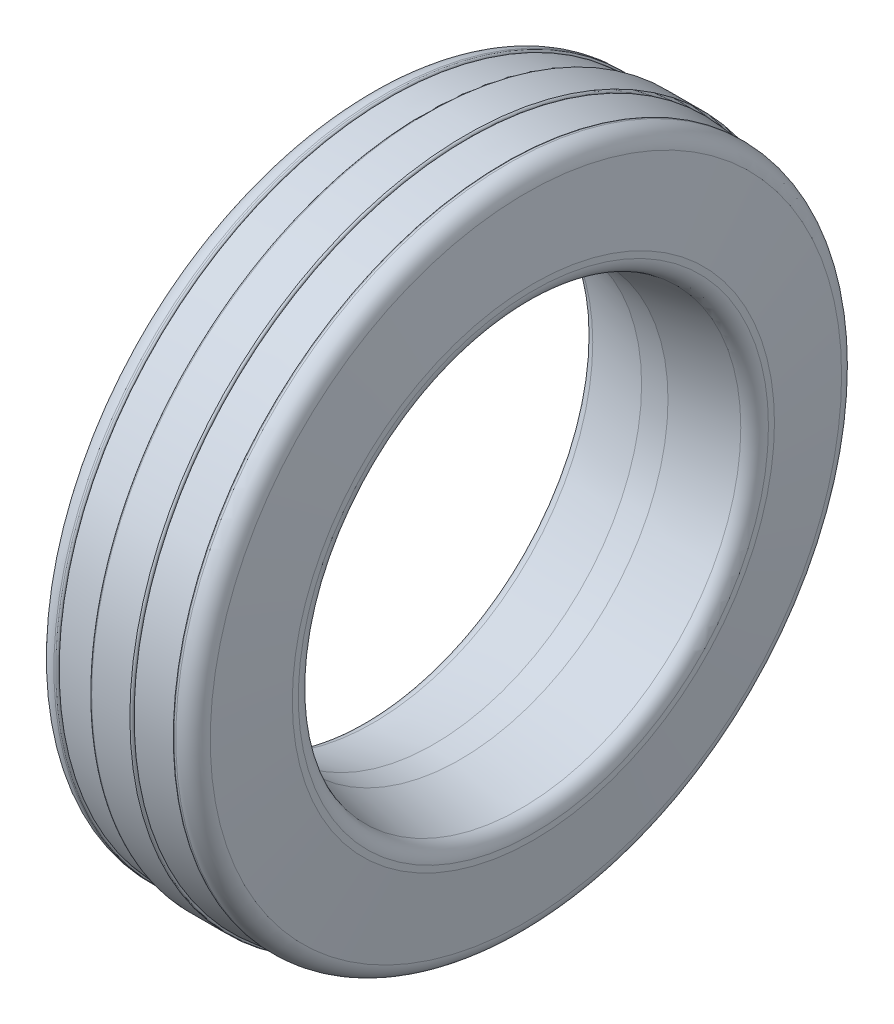
SolidWorks part; units mm, degrees
material "PE High Density"
ref_plane "Front Plane" through (0, 0, 0) normal (0, 0, 1) x (1, 0, 0)
ref_plane "Top Plane" through (0, 0, 0) normal (0, 1, 0) x (1, 0, 0)
ref_plane "Right Plane" through (0, 0, 0) normal (1, 0, 0) x (0, 0, -1)
sketch "Sketch1" plane through (0, 0, 0) normal (0, 1, 0) x (1, 0, 0)
  line L0 (0, 26.4614) -> (0, 26.5)
  line L1 (2.81, 36.5) -> (3.0064, 36.5)
  line L2 (19.0123, 26.5) -> (19.0123, 26.4614)
  line L3 (22, 0) -> (0, 0) construction
  line L4 (0, 26.4614) -> (0, 25.8384)
  line L5 (0.8199, 34.699) -> (0, 26.5)
  line L6 (19.0123, 26.4614) -> (19.0123, 25.8384)
  line L7 (18.1924, 34.699) -> (19.0123, 26.5)
  line L8 (13.8264, 36.5) -> (15.8264, 36.3)
  line L13 (5.1864, 36.5) -> (7.1864, 36.7)
  line L15 (3.1864, 36.32) -> (3.1864, 36.3)
  line L16 (16.0064, 36.5) -> (16.2023, 36.5)
  line L17 (15.8264, 36.32) -> (15.8264, 36.3)
  line L19 (13.8264, 36.5) -> (11.8264, 36.7)
  line L20 (7.4064, 36.95) -> (11.6064, 36.95)
  line L21 (7.1864, 36.7) -> (7.1864, 36.73)
  line L22 (11.8264, 36.7) -> (11.8264, 36.73)
  line L23 (3.1864, 36.3) -> (5.1864, 36.5)
  line L35 (10.9576, 22.8514) -> (17.6415, 24.1705)
  line L36 (10.9576, 22.8514) -> (8.0553, 22.8514)
  line L37 (8.0553, 22.8514) -> (1.3709, 24.1706)
  arc A0 (0.8199, 34.699) -> (2.81, 36.5) centre (2.81, 34.5) cw
  arc A1 (18.1924, 34.699) -> (16.2023, 36.5) centre (16.2023, 34.5) ccw
  arc A2 (3.1864, 36.32) -> (3.0064, 36.5) centre (3.0064, 36.32) ccw
  arc A3 (15.8264, 36.32) -> (16.0064, 36.5) centre (16.0064, 36.32) cw
  arc A8 (11.6064, 36.95) -> (11.8264, 36.73) centre (11.6064, 36.73) cw
  arc A9 (7.4064, 36.95) -> (7.1864, 36.73) centre (7.4064, 36.73) ccw
  arc A10 (17.6415, 24.1705) -> (19.0123, 25.8384) centre (17.3123, 25.8384) ccw
  arc A11 (1.3709, 24.1706) -> (0, 25.8384) centre (1.7, 25.8384) cw
  point P9 (13.8259, 23)
  point P23 (5.1864, 23)
  dimension "D1" = 2
  dimension "D6" = 0.18
  dimension "D2" = 0.22
  dimension "D4" = 1.7
  dimension "D3" = 22
revolve "Revolve1" add sketch "Sketch1" angle 360 about L3
sketch "Sketch2" plane through (0, 0, 0) normal (1, 0, 0) x (0, 0, -1)
  circle A0 centre (0, 0) radius 28 construction
  text T0 "BERO" font "Century Gothic" height 5.5
  dimension "D1" = 56
extrude "Boss-Extrude1" add sketch "Sketch2" along normal blind 10
